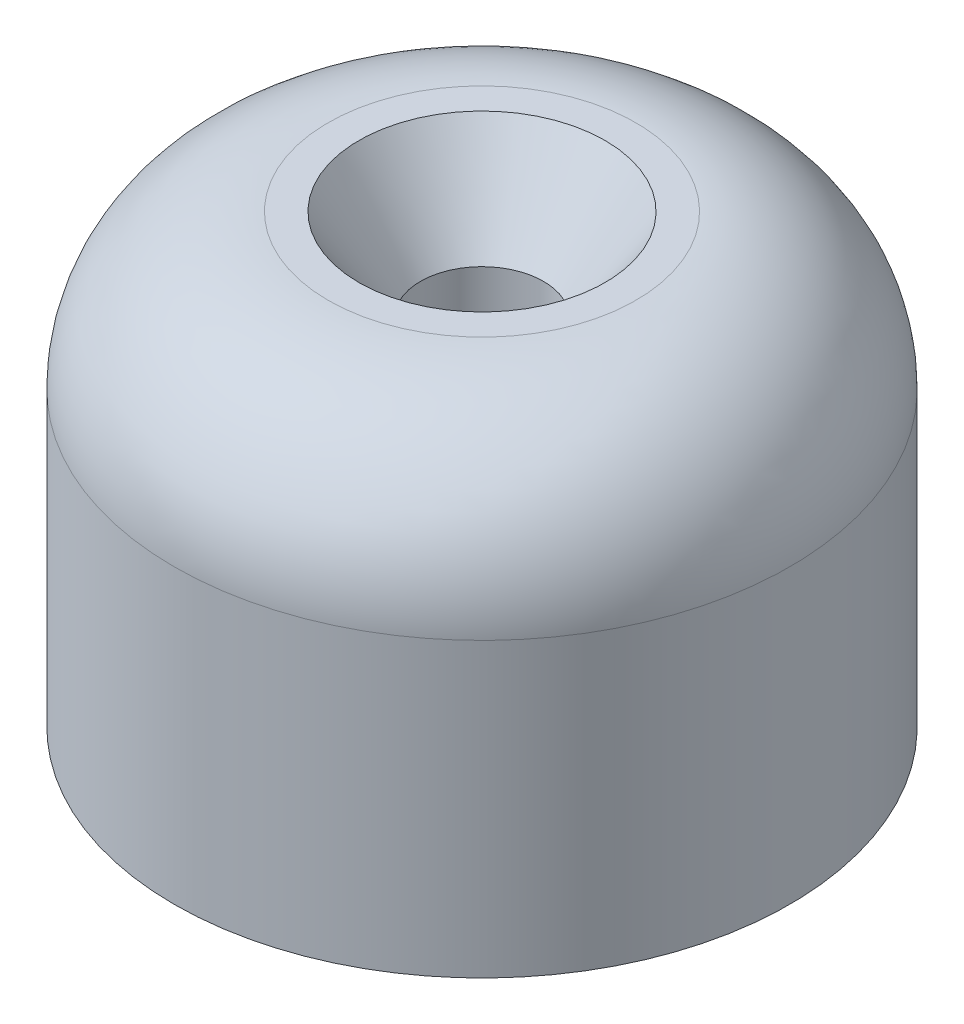
SolidWorks part; units mm, degrees
ref_plane "Front Plane" through (0, 0, 0) normal (0, 0, 1) x (1, 0, 0)
ref_plane "Top Plane" through (0, 0, 0) normal (0, 1, 0) x (1, 0, 0)
ref_plane "Right Plane" through (0, 0, 0) normal (1, 0, 0) x (0, 0, -1)
sketch "Sketch1" plane through (0, 0, 0) normal (0, 1, 0) x (1, 0, 0)
  circle A0 centre (0, 0) radius 10
  circle A1 centre (0, 0) radius 2
extrude "Boss-Extrude1" add sketch "Sketch1" along normal blind 7.5
sketch "Sketch2" plane through (0, 0, 0) normal (0, -1, 0) x (1, 0, 0)
  circle A0 centre (0, 0) radius 4.125
  circle A1 centre (0, 0) radius 10
  dimension "D1" = 8.25
extrude "Boss-Extrude2" add sketch "Sketch2" along normal blind 7
sketch "Sketch3" plane through (0, 7.5, 0) normal (0, 1, 0) x (1, 0, 0)
  circle A0 centre (0, 0) radius 4
extrude "Cut-Extrude1" cut sketch "Sketch3" against normal blind 3 draft 34 contours A0
fillet "Fillet1" radius 5 1 edges at (0, 7.5, 10)
fillet "Fillet2" radius 1 1 edges at (0, -7, -4.125)
